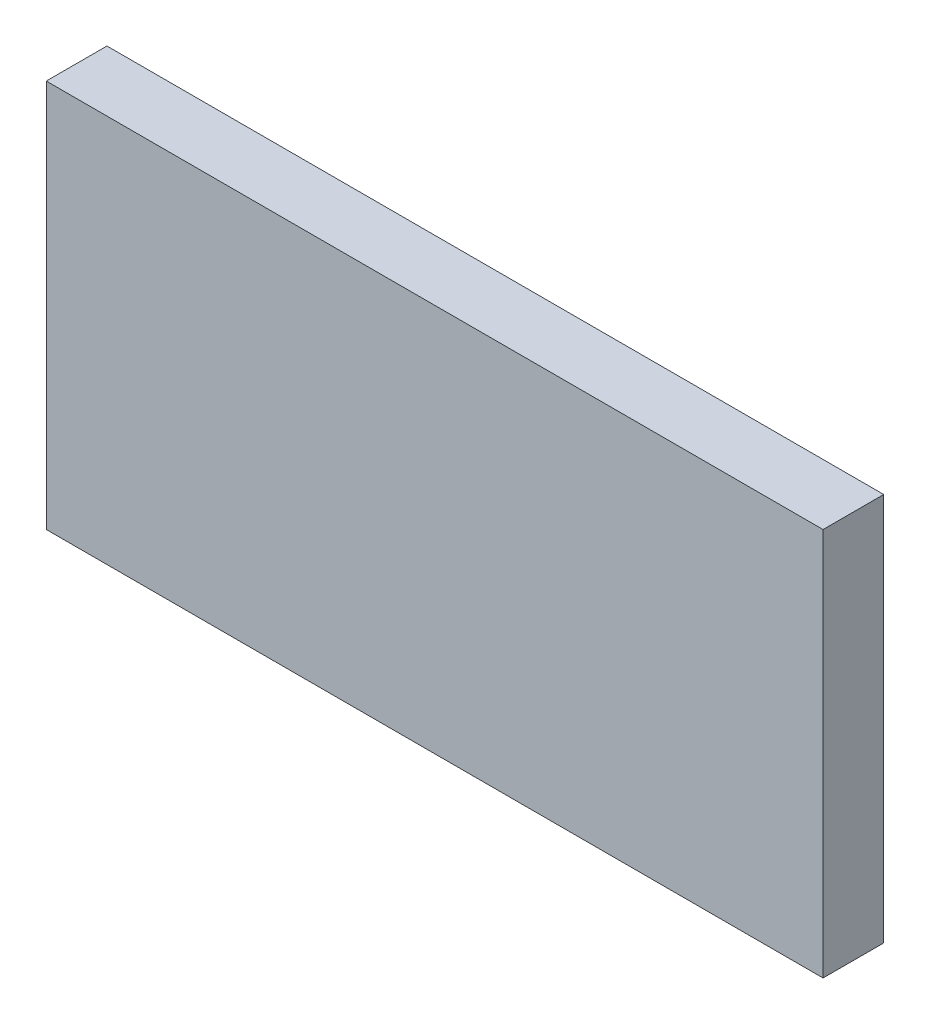
SolidWorks part; units mm, degrees
ref_plane "Front Plane" through (0, 0, 0) normal (0, 0, 1) x (1, 0, 0)
ref_plane "Top Plane" through (0, 0, 0) normal (0, 1, 0) x (1, 0, 0)
ref_plane "Right Plane" through (0, 0, 0) normal (1, 0, 0) x (0, 0, -1)
sketch "Sketch12" plane through (0, 0, 0) normal (0, 0, 1) x (1, 0, 0)
  line L1 (-32, 16) -> (32, 16)
  line L2 (-32, 16) -> (-32, -16)
  line L3 (-32, -16) -> (32, -16)
  line L4 (32, 16) -> (32, -16)
  line L5 (-32, 16) -> (32, -16) construction
  line L6 (-32, -16) -> (32, 16) construction
  point P0 (0, 0)
  dimension "D1" = 32
  dimension "D2" = 64
extrude "Boss-Extrude1" add sketch "Sketch12" along normal blind 5
sketch "Sketch14" plane through (-32, 0, 0) normal (-1, 0, 0) x (0, 0, 1)
  line L5 (2.5, 16) -> (0, 16)
  line L6 (5, 16) -> (0, 16) construction
  line L7 (0, 16) -> (0, 15.5)
  line L8 (0, 16) -> (0, -16) construction
  line L9 (0, 15.5) -> (2.5, 16)
  dimension "D1" = 0.5
